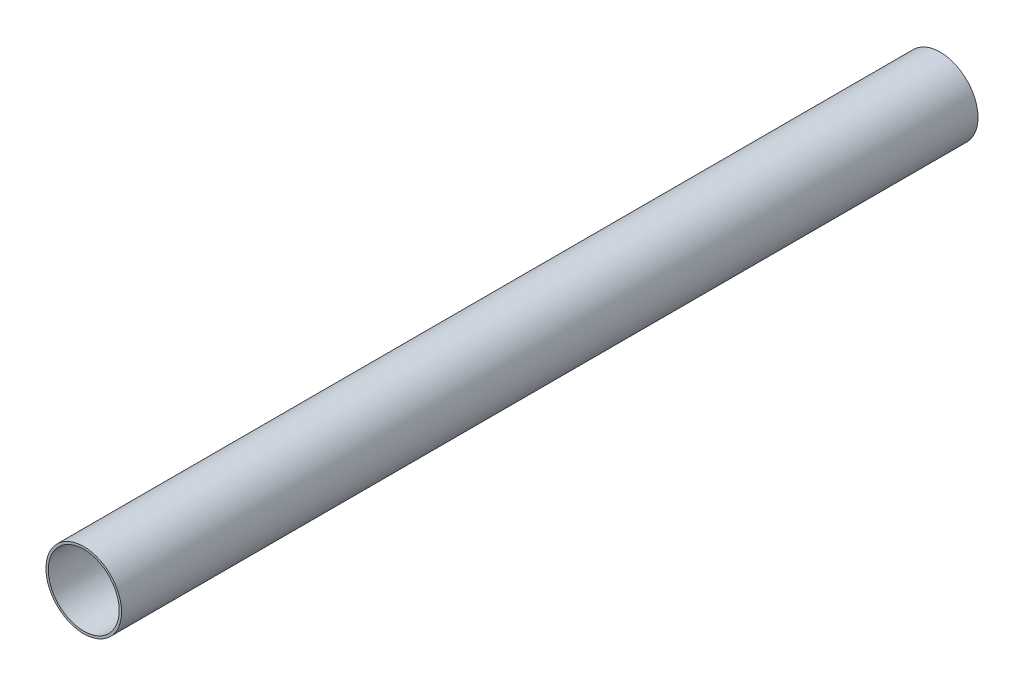
SolidWorks part; units mm, degrees
material "PC High Viscosity"
ref_plane "Front Plane" through (0, 0, 0) normal (0, 0, 1) x (1, 0, 0)
ref_plane "Top Plane" through (0, 0, 0) normal (0, 1, 0) x (1, 0, 0)
ref_plane "Right Plane" through (0, 0, 0) normal (1, 0, 0) x (0, 0, -1)
sketch "Sketch1" plane through (0, 0, 0) normal (0, 0, 1) x (1, 0, 0)
  circle A0 centre (0, 0) radius 23.8125
  circle A1 centre (0, 0) radius 25.4
  dimension "D1" = 50.8
  dimension "D2" = 47.625
extrude "Boss-Extrude1" add sketch "Sketch1" along normal mid plane 575.213
equation "\"D1@Boss-Extrude1\"=21.125in+3.625mm"
